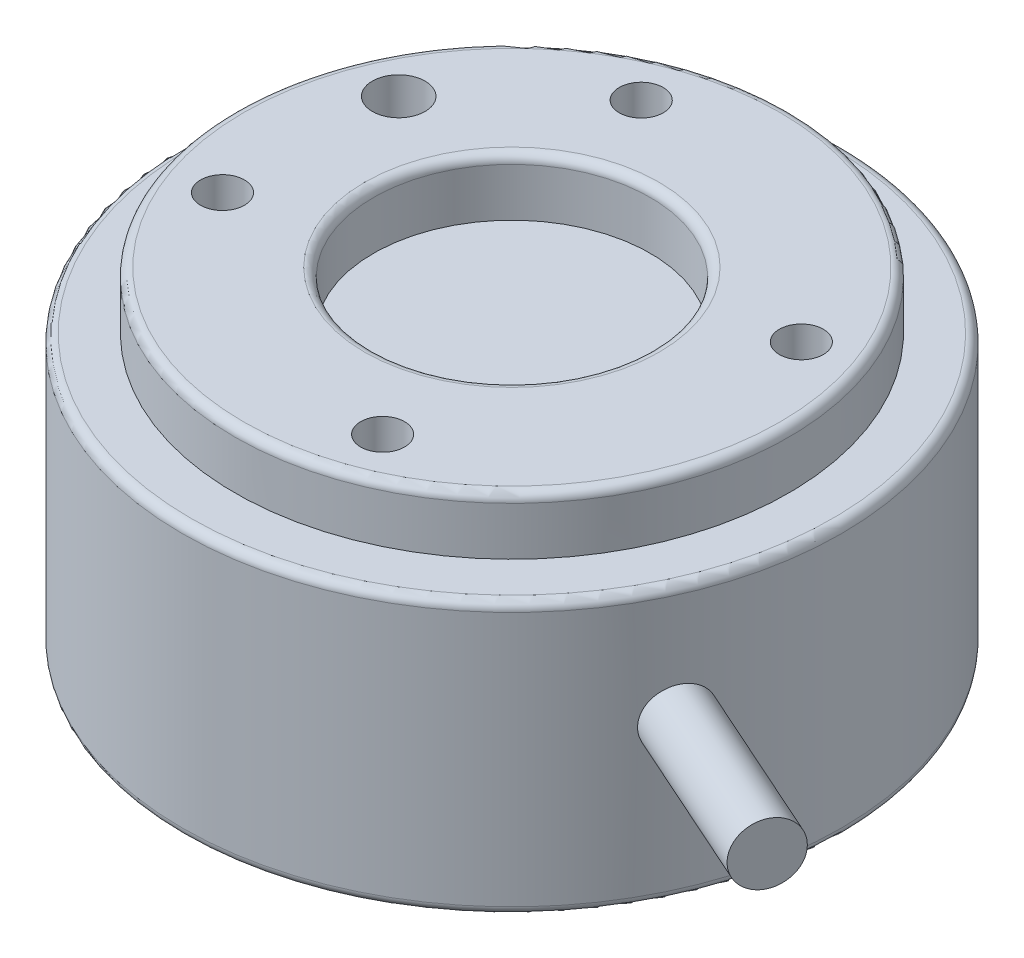
SolidWorks part; units mm, degrees
material "356.0-T6 永久成型铸件 (SS)"
ref_plane "前视基准面" through (0, 0, 0) normal (0, 0, 1) x (1, 0, 0)
ref_plane "上视基准面" through (0, 0, 0) normal (0, 1, 0) x (1, 0, 0)
ref_plane "右视基准面" through (0, 0, 0) normal (1, 0, 0) x (0, 0, -1)
sketch "草图1" plane through (0, 0, 0) normal (0, 1, 0) x (1, 0, 0)
  circle A0 centre (0, 0) radius 37.5
extrude "凸台-拉伸1" add sketch "草图1" along normal blind 31
sketch "草图2" plane through (0, 31, 0) normal (0, 1, 0) x (1, 0, 0)
  circle A0 centre (0, 0) radius 31.5
extrude "凸台-拉伸2" add sketch "草图2" along normal blind 6.5
sketch "草图3" plane through (0, 37.5, 0) normal (0, 1, 0) x (1, 0, 0)
  circle A0 centre (0, 0) radius 15.75
extrude "切除-拉伸1" cut sketch "草图3" against normal blind 6.5
sketch "草图4" plane through (0, 0, 0) normal (0, -1, 0) x (1, 0, 0)
  circle A0 centre (0, 0) radius 15.8
extrude "凸台-拉伸3" add sketch "草图4" along normal blind 6.2
sketch "草图8" plane through (0, 37.5, 0) normal (0, 1, 0) x (1, 0, 0)
  line L0 (-23.8181, -9.1075) -> (23.8181, 9.1075) construction
  line L1 (-9.1075, 23.8181) -> (9.1075, -23.8181) construction
  line L2 (0, 0) -> (-23.2819, 10.402) construction
  line L3 (0, 0) -> (10.402, 23.2819) construction
  circle A1 centre (0, 0) radius 25.5 construction
  dimension "D1" = 45
  dimension "D2" = 90
hole_wizard "M6 螺纹孔1" positions "草图12" profile "草图11" tap size "M6" standard "GB" end condition up to next
sketch "草图12" plane through (0, 37.5, 0) normal (0, 1, 0) x (1, 0, 0)
  point P0 (-23.8181, -9.1075)
  point P3 (9.1075, -23.8181)
  point P6 (23.8181, 9.1075)
  point P9 (-9.1075, 23.8181)
sketch "草图11" plane through (-23.8181, 37.5, 9.1075) normal (1, 0, 0) x (0, 0, 1)
  line L0 (0, 0) -> (0, 37.5)
  line L1 (0, 37.5) -> (2.5, 37.5)
  line L2 (2.5, 37.5) -> (2.5, 0)
  line L5 (2.5, 0) -> (0, 0)
  line L11 (0, -6.35) -> (0, 107.95) construction
  dimension "通孔螺纹孔钻头直径" = 5
  dimension "通孔螺纹孔钻头深度" = 37.5
cosmetic thread "孔螺蚊线1" parameters "D2"=6
cosmetic thread "孔螺蚊线2" parameters "D2"=6
cosmetic thread "孔螺蚊线3" parameters "D2"=6
cosmetic thread "孔螺蚊线4" parameters "D2"=6
hole_wizard "大小mm 暗销孔1" positions "草图14" profile "草图13" hole size "Ø6.0" standard "GB"
sketch "草图14" plane through (0, 37.5, 0) normal (0, 1, 0) x (1, 0, 0)
  point P0 (-23.2819, 10.402)
sketch "草图13" plane through (-23.2819, 37.5, -10.402) normal (1, 0, 0) x (0, 0, 1)
  line L0 (0, 0) -> (0, 7.8026)
  line L1 (0, 7.8026) -> (3, 6)
  line L2 (3, 6) -> (3, 0)
  line L5 (3, 0) -> (0, 0)
  line L10 (0, 7.8026) -> (-3, 6) construction
  line L11 (0, -6.35) -> (0, 107.95) construction
  dimension "孔直径" = 6
  dimension "孔深度" = 6
  dimension "导头角度" = 118
ref_plane "基准面1" through (34.2381, 0, 15.297) normal (0.913, 0, 0.4079) x (0.4079, 0, -0.913)
ref_plane "基准面2" through (52.4985, 0, 23.4555) normal (0.913, 0, 0.4079) x (0.4079, 0, -0.913)
sketch "草图16" plane through (52.4985, 0, 23.4555) normal (0.913, 0, 0.4079) x (0.4079, 0, -0.913)
  circle A0 centre (0, 17.6985) radius 3.4578
extrude "凸台-拉伸4" add sketch "草图16" against normal up to next
fillet "圆角2" radius 1 4 edges at (0, 37.5, 31.5) (0, 37.5, 15.75) (0, 31, 37.5) (0, 0, 37.5)
ref_point "点1"
ref_point "点2"
